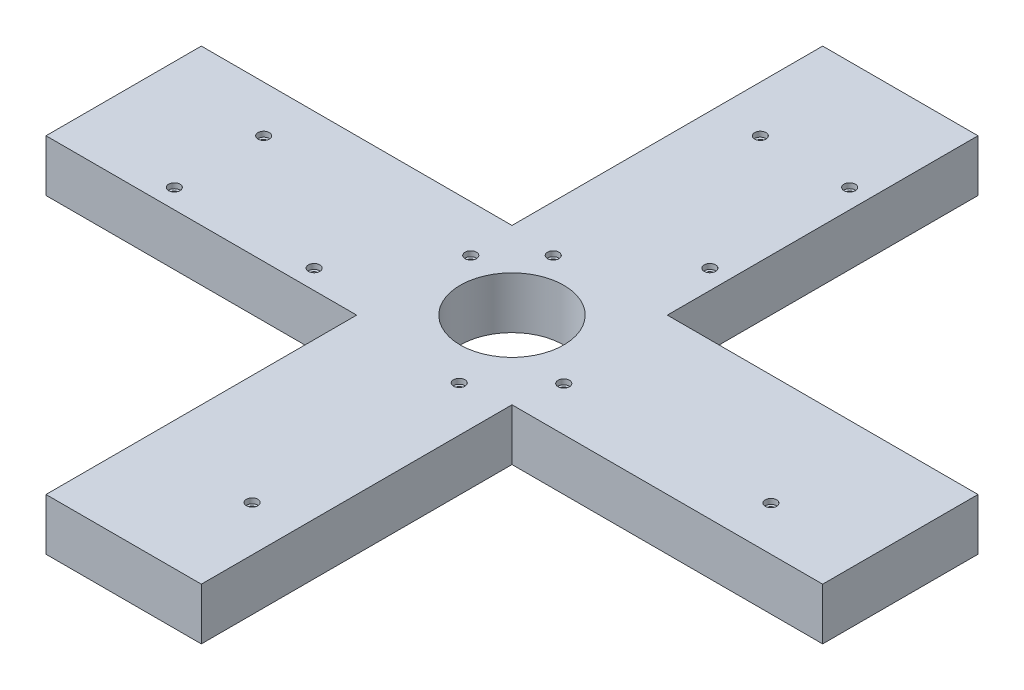
SolidWorks part; units mm, degrees
ref_plane "Front Plane" through (0, 0, 0) normal (0, 0, 1) x (1, 0, 0)
ref_plane "Top Plane" through (0, 0, 0) normal (0, 1, 0) x (1, 0, 0)
ref_plane "Right Plane" through (0, 0, 0) normal (1, 0, 0) x (0, 0, -1)
sketch "Sketch1" plane through (0, 0, 0) normal (0, 1, 0) x (1, 0, 0)
  line L1 (-150, 150) -> (150, 150)
  line L2 (-150, 150) -> (-150, -150)
  line L3 (-150, -150) -> (150, -150)
  line L4 (150, 150) -> (150, -150)
  line L5 (-150, 150) -> (150, -150) construction
  line L6 (-150, -150) -> (150, 150) construction
  point P0 (0, 0)
  dimension "D1" = 300
  dimension "D2" = 300
extrude "Boss-Extrude1" add sketch "Sketch1" along normal blind 20
sketch "Sketch2" plane through (0, 20, 0) normal (0, 1, 0) x (1, 0, 0)
  line L1 (-150, 150) -> (-30, 150)
  line L2 (-150, 150) -> (-150, 30)
  line L3 (-150, 30) -> (-30, 30)
  line L4 (-30, 150) -> (-30, 30)
  line L5 (150, 150) -> (30, 150)
  line L6 (150, 150) -> (150, 30)
  line L7 (150, 30) -> (30, 30)
  line L8 (30, 150) -> (30, 30)
  line L9 (-150, -150) -> (-30, -150)
  line L10 (-150, -150) -> (-150, -30)
  line L11 (-150, -30) -> (-30, -30)
  line L12 (-30, -150) -> (-30, -30)
  line L13 (150, -150) -> (30, -150)
  line L14 (150, -150) -> (150, -30)
  line L15 (150, -30) -> (30, -30)
  line L16 (30, -150) -> (30, -30)
  dimension "D1" = 120
  dimension "D2" = 120
  dimension "D3" = 120
  dimension "D4" = 120
  dimension "D5" = 120
  dimension "D6" = 120
  dimension "D7" = 120
extrude "Cut-Extrude1" cut sketch "Sketch2" against normal through all
hole_wizard "CBORE for M2 SHCS1" positions "Sketch6" profile "Sketch5" counterbore size "M2" standard "ANSI Metric" end condition through all
sketch "Sketch6" plane through (0, 20, 0) normal (0, 1, 0) x (1, 0, 0)
  point P0 (-53.93, -22.5)
  point P2 (-107.93, -22.5)
  point P4 (32.88, -12.88)
  point P6 (112.88, -12.88)
  dimension "D1" = 22.5
  dimension "D2" = 22.5
  dimension "D3" = 12.88
  dimension "D4" = 12.88
  dimension "D5" = 53.93
  dimension "D7" = 32.88
  dimension "D8" = 80
sketch "Sketch5" plane through (-53.93, 20, 22.5) normal (1, 0, 0) x (0, 0, 1)
  line L0 (0, 0) -> (0, 20)
  line L1 (0, 20) -> (1.2, 20)
  line L3 (1.2, 20) -> (1.2, 2)
  line L4 (1.2, 2) -> (2.2, 2)
  line L5 (2.2, 2) -> (2.2, 0)
  line L7 (2.2, 0) -> (0, 0)
  line L11 (0, -6.35) -> (0, 107.95) construction
  dimension "Thru Hole Dia." = 2.4
  dimension "Thru Hole Depth" = 20
  dimension "C'Bore Dia." = 4.4
  dimension "C'Bore Depth" = 2
hole_wizard "CBORE for M2 SHCS2" positions "Sketch8" profile "Sketch7" counterbore size "M2" standard "ANSI Metric" end condition through all
sketch "Sketch8" plane through (0, 20, 0) normal (0, 1, 0) x (1, 0, 0)
  point P0 (22.5, 53.93)
  point P2 (22.5, 107.93)
  point P4 (12.5, -32.88)
  point P6 (12.5, -112.88)
  dimension "D1" = 22.5
  dimension "D2" = 22.5
  dimension "D3" = 53.93
  dimension "D5" = 12.5
  dimension "D6" = 12.5
  dimension "D7" = 32.88
  dimension "D8" = 80
sketch "Sketch7" plane through (22.5, 20, -53.93) normal (1, 0, 0) x (0, 0, 1)
  line L0 (0, 0) -> (0, 20)
  line L1 (0, 20) -> (1.2, 20)
  line L3 (1.2, 20) -> (1.2, 2)
  line L4 (1.2, 2) -> (2.2, 2)
  line L5 (2.2, 2) -> (2.2, 0)
  line L7 (2.2, 0) -> (0, 0)
  line L11 (0, -6.35) -> (0, 107.95) construction
  dimension "Thru Hole Dia." = 2.4
  dimension "Thru Hole Depth" = 20
  dimension "C'Bore Dia." = 4.4
  dimension "C'Bore Depth" = 2
hole_wizard "CBORE for M2 SHCS3" positions "Sketch10" profile "Sketch9" counterbore size "M2" standard "ANSI Metric" end condition through all
sketch "Sketch10" plane through (0, 20, 0) normal (0, 1, 0) x (1, 0, 0)
  circle A1 centre (-107.93, -22.5) radius 1.2 construction
  circle A4 centre (22.5, 107.93) radius 1.2 construction
  circle A5 centre (-53.93, -22.5) radius 2.2 construction
  circle A6 centre (22.5, 53.93) radius 1.2 construction
  point P0 (-27.93, 12)
  point P2 (-107.93, 12)
  point P4 (-12, 27.93)
  point P6 (-12, 107.93)
  dimension "D1" = 27.93
  dimension "D2" = 0
  dimension "D3" = 34.5
  dimension "D4" = 34.5
  dimension "D5" = 27.93
  dimension "D6" = 0
  dimension "D7" = 34.5
  dimension "D8" = 34.5
sketch "Sketch9" plane through (-27.93, 20, -12) normal (1, 0, 0) x (0, 0, 1)
  line L0 (0, 0) -> (0, 20)
  line L1 (0, 20) -> (1.2, 20)
  line L3 (1.2, 20) -> (1.2, 2)
  line L4 (1.2, 2) -> (2.2, 2)
  line L5 (2.2, 2) -> (2.2, 0)
  line L7 (2.2, 0) -> (0, 0)
  line L11 (0, -6.35) -> (0, 107.95) construction
  dimension "Thru Hole Dia." = 2.4
  dimension "Thru Hole Depth" = 20
  dimension "C'Bore Dia." = 4.4
  dimension "C'Bore Depth" = 2
sketch "Sketch12" plane through (0, 20, 0) normal (0, 1, 0) x (1, 0, 0)
  circle A0 centre (0, 0) radius 20
extrude "Cut-Extrude2" cut sketch "Sketch12" against normal through all
